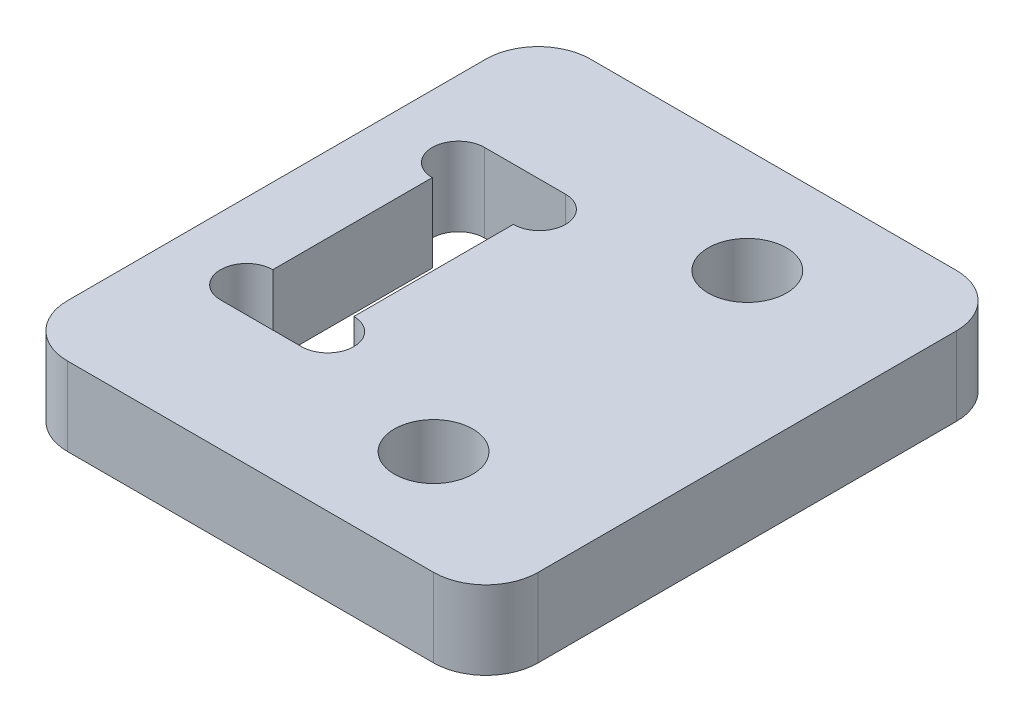
SolidWorks part; units mm, degrees
material "Thornel Mat VMA"
ref_plane "前视基准面" through (0, 0, 0) normal (0, 0, 1) x (1, 0, 0)
ref_plane "上视基准面" through (0, 0, 0) normal (0, 1, 0) x (1, 0, 0)
ref_plane "右视基准面" through (0, 0, 0) normal (1, 0, 0) x (0, 0, -1)
sketch "草图1" plane through (0, 0, 0) normal (0, 1, 0) x (1, 0, 0)
  line L0 (0, 0) -> (6, 0) construction
  line L1 (-6, -10) -> (6, -10)
  line L2 (-6, -10) -> (-6, 10) construction
  line L3 (-6, 10) -> (6, 10)
  line L4 (6, -10) -> (6, 10)
  line L5 (-6, -10) -> (6, 10) construction
  line L6 (-6, 10) -> (6, -10) construction
  line L7 (0, 6) -> (0, -6) construction
  line L8 (-7.55, 0) -> (-7.55, -5.05) construction
  line L9 (-6, 10) -> (-12, 10)
  line L10 (-6, 10) -> (-6, -10) construction
  line L11 (-6, -10) -> (-12, -10)
  line L12 (-12, 10) -> (-12, -10)
  line L13 (-9, -10) -> (-9, 10) construction
  line L14 (-6, 0) -> (-12, 0) construction
  line L15 (-9.1, -5.05) -> (-6, -5.05)
  line L16 (-9.1, -5.05) -> (-9.1, 5.05)
  line L17 (-9.1, 5.05) -> (-6, 5.05)
  line L18 (-6, -5.05) -> (-6, 5.05)
  line L19 (-9.1, -5.05) -> (-6, 5.05) construction
  line L20 (-9.1, 5.05) -> (-6, -5.05) construction
  circle A0 centre (0, 6) radius 1.5
  circle A1 centre (0, -6) radius 1.5
  circle A2 centre (-6, -4.05) radius 1
  circle A3 centre (-6, 4.05) radius 1
  circle A4 centre (-9.1, 4.05) radius 1
  circle A5 centre (-9.1, -4.05) radius 1
  point P0 (0, 0)
  point P15 (-7.55, 0)
  point P250 (-9, 0)
  dimension "D1" = 3
  dimension "D8" = 2
  dimension "D2" = 12
  dimension "D3" = 20
  dimension "D4" = 12
  dimension "D5" = 3.1
  dimension "D6" = 10.1
  dimension "D7" = 6
extrude "凸台-拉伸1" add sketch "草图1" along normal blind 3 contours L9 L12 L11 L1 L4 L3 A0 A1 L15 A5 L16 A4 L17 A3 L18 A2
fillet "圆角1" radius 2 4 edges at (6, 1.5, -10) (6, 1.5, 10) (-12, 1.5, 10) (-12, 1.5, -10)
